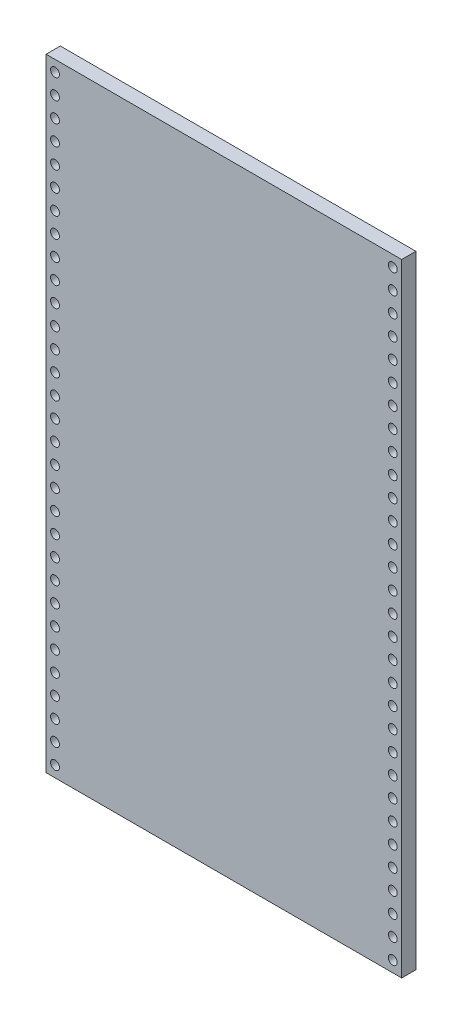
SolidWorks part; units mm, degrees
ref_plane "Front Plane" through (0, 0, 0) normal (0, 0, 1) x (1, 0, 0)
ref_plane "Top Plane" through (0, 0, 0) normal (0, 1, 0) x (1, 0, 0)
ref_plane "Right Plane" through (0, 0, 0) normal (1, 0, 0) x (0, 0, -1)
sketch "Sketch1" plane through (0, 0, 0) normal (0, 0, 1) x (1, 0, 0)
  line L1 (-200, 0) -> (200, 0)
  line L2 (-200, 0) -> (-200, 700)
  line L3 (-200, 700) -> (200, 700)
  line L4 (200, 0) -> (200, 700)
  point P4 (0, 0)
  dimension "D1" = 400
  dimension "D2" = 700
extrude "Boss-Extrude1" add sketch "Sketch1" along normal blind 16
sketch "Sketch2" plane through (0, 0, 16) normal (0, 0, 1) x (1, 0, 0)
  circle A0 centre (190, 12.5) radius 5
sketch "Sketch3" plane through (0, 0, 16) normal (0, 0, 1) x (1, 0, 0)
  line L0 (0, 0) -> (0, 700) construction
  line L1 (200, 700) -> (-200, 700) construction
ref_plane "Plane1" through (0, 0, 0) normal (1, 0, 0) x (0, 0, -1)
extrude "Cut-Extrude1" cut sketch "Sketch2" along normal through all and the other way through all
pattern_linear "LPattern1" count 31 spacing 22.5 along (0, 1, 0) of "Cut-Extrude1"
mirror "Mirror1" about plane through (0, 0, 0) normal (1, 0, 0) of "LPattern1", "Cut-Extrude1"
